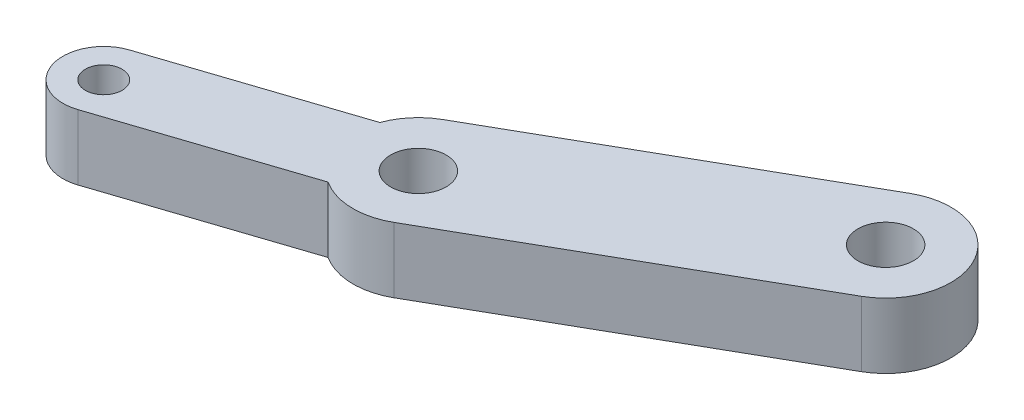
SolidWorks part; units mm, degrees
ref_plane "Front Plane" through (0, 0, 0) normal (0, 0, 1) x (1, 0, 0)
ref_plane "Top Plane" through (0, 0, 0) normal (0, 1, 0) x (1, 0, 0)
ref_plane "Right Plane" through (0, 0, 0) normal (1, 0, 0) x (0, 0, -1)
sketch "Sketch1" plane through (0, 0, 0) normal (0, 1, 0) x (1, 0, 0)
  line L0 (47.2297, 219.0186) -> (732.563, 219.0186) construction
  line L1 (1.3614, 8.3834) -> (15.8307, 13.1826) construction
  line L2 (0.5744, 10.7563) -> (12.0799, 14.5725)
  line L3 (2.1485, 6.0105) -> (13.654, 9.8267)
  line L4 (15.8307, 13.1826) -> (34.0568, 23.5731) construction
  line L5 (13.8497, 16.6576) -> (32.0757, 27.0481)
  line L6 (17.8118, 9.7077) -> (36.0378, 20.0981)
  circle A0 centre (15.8307, 13.1826) radius 1.7
  circle A1 centre (1.3614, 8.3834) radius 1.125
  arc A2 (0.5744, 10.7563) -> (2.1485, 6.0105) centre (1.3614, 8.3834) ccw
  circle A3 centre (34.0568, 23.5731) radius 1.7
  arc A5 (13.8497, 16.6576) -> (12.0799, 14.5725) centre (15.8307, 13.1826) ccw
  arc A6 (36.0378, 20.0981) -> (32.0757, 27.0481) centre (34.0568, 23.5731) ccw
  arc A7 (13.654, 9.8267) -> (17.8118, 9.7077) centre (15.8307, 13.1826) ccw
  point P6 (8.5961, 10.783)
  point P14 (24.9437, 18.3779)
extrude "Boss-Extrude1" add sketch "Sketch1" along normal blind 4
